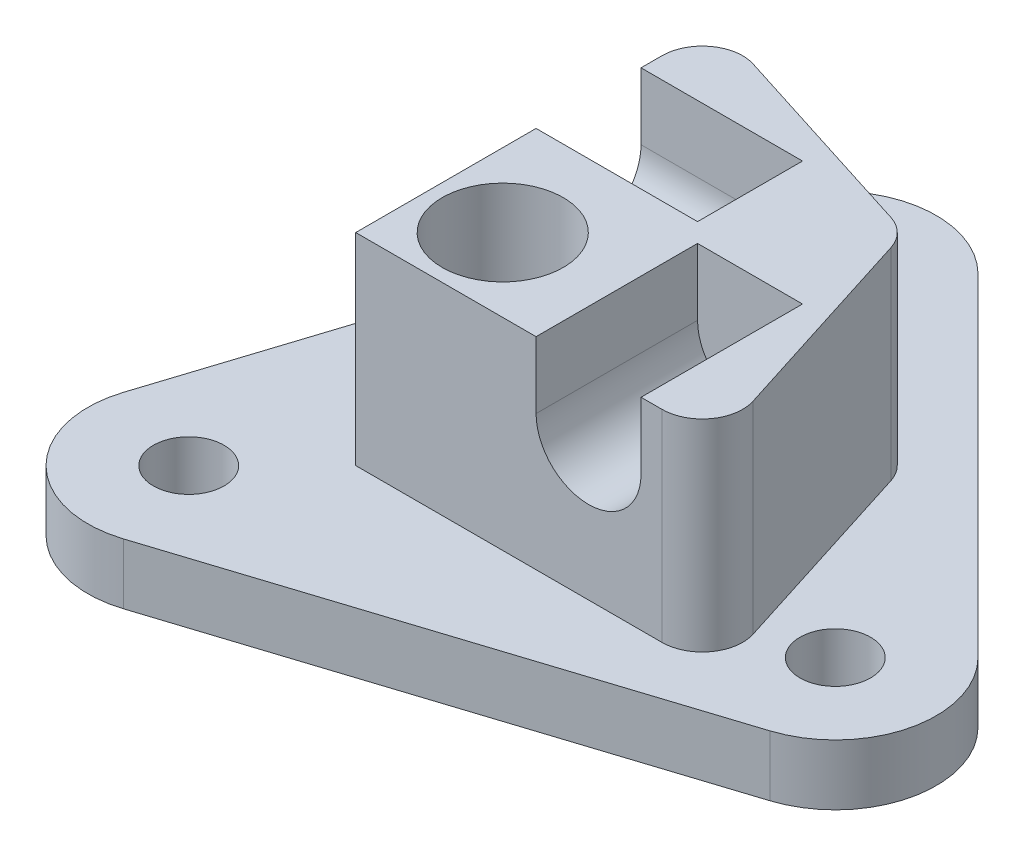
SolidWorks part; units mm, degrees
ref_plane "前视基准面" through (0, 0, 0) normal (0, 0, 1) x (1, 0, 0)
ref_plane "上视基准面" through (0, 0, 0) normal (0, 1, 0) x (1, 0, 0)
ref_plane "右视基准面" through (0, 0, 0) normal (1, 0, 0) x (0, 0, -1)
sketch "草图1" plane through (0, 0, 0) normal (0, 1, 0) x (1, 0, 0)
  line L2 (0, 16.4742) -> (0, 0) construction
  line L7 (0, 16.4742) -> (16.4742, 0) construction
  line L8 (16.4742, 0) -> (0, 0) construction
  line L17 (8.2371, 8.2371) -> (0, 0) construction
  line L18 (0, 16.4742) -> (-7.7782, -7.7782)
  line L19 (-7.7782, -7.7782) -> (16.4742, 0)
  line L20 (-6.2512, -12.5393) -> (18.0012, -4.7611)
  line L21 (3.5355, 20.0097) -> (20.0097, 3.5355)
  line L22 (-4.7611, 18.0012) -> (-12.5393, -6.2512)
  line L23 (-15.5082, -15.5082) -> (25.8039, -2.2586) construction
  line L24 (-2.2586, 25.8039) -> (25.8039, -2.2586) construction
  line L25 (-2.2586, 25.8039) -> (-15.5082, -15.5082) construction
  circle A0 centre (0, 0) radius 3
  circle A1 centre (0, 16.4742) radius 1.75
  circle A6 centre (16.4742, 0) radius 1.75
  circle A10 centre (-7.7782, -7.7782) radius 1.75
  arc A11 (18.0012, -4.7611) -> (20.0097, 3.5355) centre (16.4742, 0) ccw
  arc A12 (3.5355, 20.0097) -> (-4.7611, 18.0012) centre (0, 16.4742) ccw
  arc A13 (-6.2512, -12.5393) -> (-12.5393, -6.2512) centre (-7.7782, -7.7782) cw
  dimension "D1" = 23.298
  dimension "D6" = 3.5
  dimension "D2" = 6
  dimension "D5" = 5
  dimension "D3" = 11
  dimension "D4" = 5
extrude "凸台-拉伸1" add sketch "草图1" along normal blind 3
sketch "草图4" plane through (0, 3, 0) normal (0, 1, 0) x (1, 0, 0)
  line L14 (-3.6416, 11.53) -> (-3.6416, -3.6416)
  line L15 (-3.6416, -3.6416) -> (11.53, -3.6416)
  line L16 (12.9442, -0.2274) -> (-0.2274, 12.9442)
  line L17 (3.5355, 20.0097) -> (20.0097, 3.5355) construction
  line L18 (6.3584, 6.3584) -> (-3.6416, -3.6416) construction
  line L20 (2.3584, 10.3584) -> (8.3584, 10.3584)
  line L23 (-1.037, 13.4364) -> (8.963, 10.2648)
  line L24 (10.3584, 8.3584) -> (10.3584, 2.3584)
  line L25 (0, 0) -> (16.4742, 0) construction
  line L26 (10.493, 4.3584) -> (10.493, -3.6416)
  line L27 (5.293, 4.3584) -> (10.493, 4.3584)
  line L28 (5.293, 4.3584) -> (5.293, -3.6416)
  line L29 (4.3584, 10.493) -> (-3.6416, 10.493)
  line L30 (4.3584, 5.293) -> (-3.6416, 5.293)
  line L31 (4.3584, 5.293) -> (4.3584, 10.493)
  line L32 (7.893, 4.3584) -> (7.893, -14.3882) construction
  line L33 (13.4364, -1.037) -> (10.2648, 8.963)
  circle A0 centre (0, 0) radius 3 construction
  circle A1 centre (0, 0) radius 3
  circle A2 centre (16.4742, 0) radius 1.75 construction
  arc A3 (8.3584, 10.3584) -> (10.3584, 8.3584) centre (8.3584, 8.3584) cw
  arc A4 (11.53, -3.6416) -> (12.9442, -0.2274) centre (11.53, -1.6416) ccw
  arc A5 (-3.6416, 11.53) -> (-0.2274, 12.9442) centre (-1.6416, 11.53) cw
  point P4 (11.7726, 11.7726)
  point P41 (10.3584, 10.3584)
  point P44 (16.3584, -3.6416)
  dimension "D8" = 2
  dimension "D1" = 20
  dimension "D2" = 8
  dimension "D3" = 5.2
  dimension "D4" = 7.893
  dimension "D5" = 8.5812
  dimension "D6" = 8
  dimension "D7" = 2
extrude "凸台-拉伸3" add sketch "草图4" along normal blind 10
sketch "草图8" plane through (0, 0, 3.6416) normal (0, 0, 1) x (1, 0, 0)
  line L0 (7.893, 5) -> (7.893, -3.886) construction
  line L2 (-6.2512, 0) -> (18.0012, 0) construction
  line L10 (-3.6416, 3) -> (5.293, 3) construction
  line L11 (5.293, 9.7) -> (10.493, 9.7)
  line L12 (5.293, 9.7) -> (5.293, 3)
  line L13 (5.293, 3) -> (10.493, 3)
  line L14 (10.493, 9.7) -> (10.493, 3)
  circle A0 centre (7.893, 9.7) radius 2.6
  point P4 (7.893, 3)
  dimension "D1" = 5.2
  dimension "D2" = 9.7
extrude "凸台-拉伸5" add sketch "草图8" against normal up to next
ref_plane "基准面2" through (0, 0, 0) normal (0.7071, 0, 0.7071) x (0.7071, 0, -0.7071)
mirror "镜向7" about plane through (0, 0, 0) normal (0.7071, 0, 0.7071) of "凸台-拉伸5"
